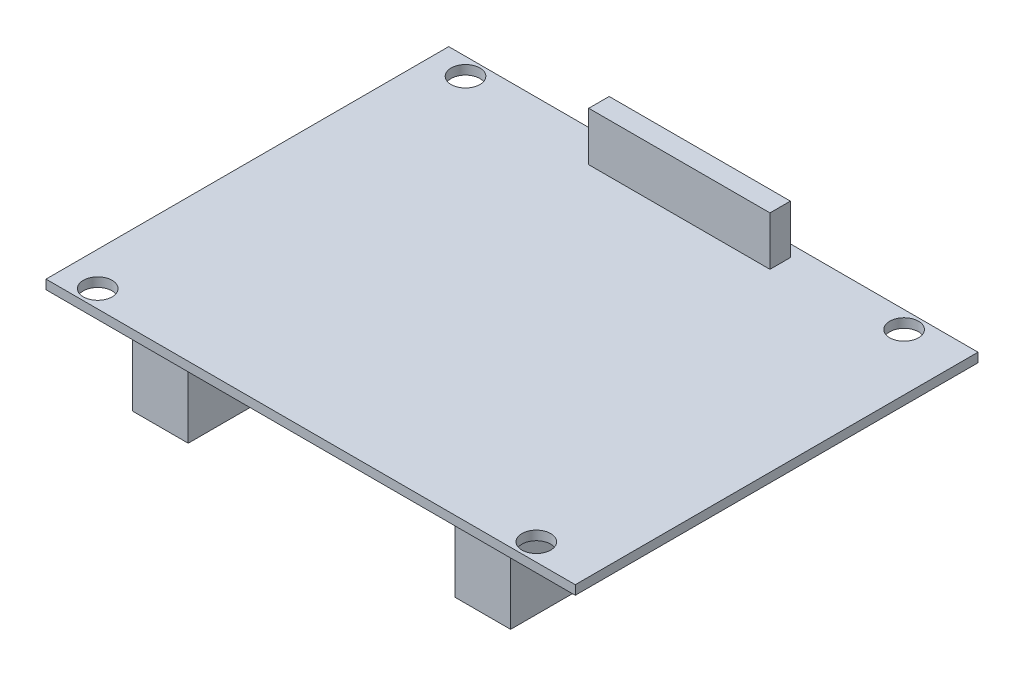
SolidWorks part; units mm, degrees
ref_plane "Front Plane" through (0, 0, 0) normal (0, 0, 1) x (1, 0, 0)
ref_plane "Top Plane" through (0, 0, 0) normal (0, 1, 0) x (1, 0, 0)
ref_plane "Right Plane" through (0, 0, 0) normal (1, 0, 0) x (0, 0, -1)
sketch "Sketch1" plane through (0, 0, 0) normal (0, 1, 0) x (1, 0, 0)
  line L1 (0, 0) -> (92, 0)
  line L2 (0, 0) -> (0, 70)
  line L3 (0, 70) -> (92, 70)
  line L4 (92, 0) -> (92, 70)
  circle A0 centre (5.92, 3.07) radius 2.5
  circle A1 centre (82.16, 3.07) radius 2.5
  circle A2 centre (82.16, 67) radius 2.5
  circle A3 centre (5.92, 67) radius 2.5
  dimension "D5" = 9.84
  dimension "D7" = 9.84
  dimension "D9" = 3
  dimension "D1" = 92
  dimension "D2" = 70
  dimension "D3" = 5.92
  dimension "D4" = 3.07
  dimension "D6" = 3.07
  dimension "D8" = 3
  dimension "D10" = 5.92
extrude "Y+ PCB extr" add sketch "Sketch1" along normal blind 1.6
sketch "Sketch2" plane through (0, 1.6, 0) normal (0, 1, 0) x (1, 0, 0)
  line L0 (92, 70) -> (0, 70) construction
  line L1 (29.95, 67.94) -> (61.45, 67.94)
  line L2 (29.95, 67.94) -> (29.95, 64.39)
  line L3 (29.95, 64.39) -> (61.45, 64.39)
  line L4 (61.45, 67.94) -> (61.45, 64.39)
  line L5 (0, 70) -> (0, 0) construction
  dimension "D1" = 2.06
  dimension "D2" = 29.95
  dimension "D3" = 31.5
  dimension "D4" = 3.55
extrude "Y+ header extr" add sketch "Sketch2" along normal blind 8.5
sketch "Sketch3" plane through (0, 0, 0) normal (0, -1, 0) x (1, 0, 0)
  line L0 (92, 0) -> (92, -70) construction
  line L1 (78.63, -65.08) -> (68.92, -65.08)
  line L2 (78.63, -65.08) -> (78.63, -2.13)
  line L3 (78.63, -2.13) -> (68.92, -2.13)
  line L4 (68.92, -65.08) -> (68.92, -2.13)
  line L5 (22.59, -65.19) -> (12.88, -65.19)
  line L6 (22.59, -65.19) -> (22.59, -2.13)
  line L7 (22.59, -2.13) -> (12.88, -2.13)
  line L8 (12.88, -65.19) -> (12.88, -2.13)
  line L9 (92, -70) -> (0, -70) construction
  line L10 (0, 0) -> (92, 0) construction
  line L11 (0, -70) -> (0, 0) construction
  dimension "D1" = 13.37
  dimension "D2" = 4.92
  dimension "D3" = 2.13
  dimension "D4" = 9.71
  dimension "D5" = 12.88
  dimension "D6" = 4.81
  dimension "D7" = 2.13
  dimension "D8" = 9.71
extrude "Y- MOLEX power extr" add sketch "Sketch3" along normal blind 12.88
